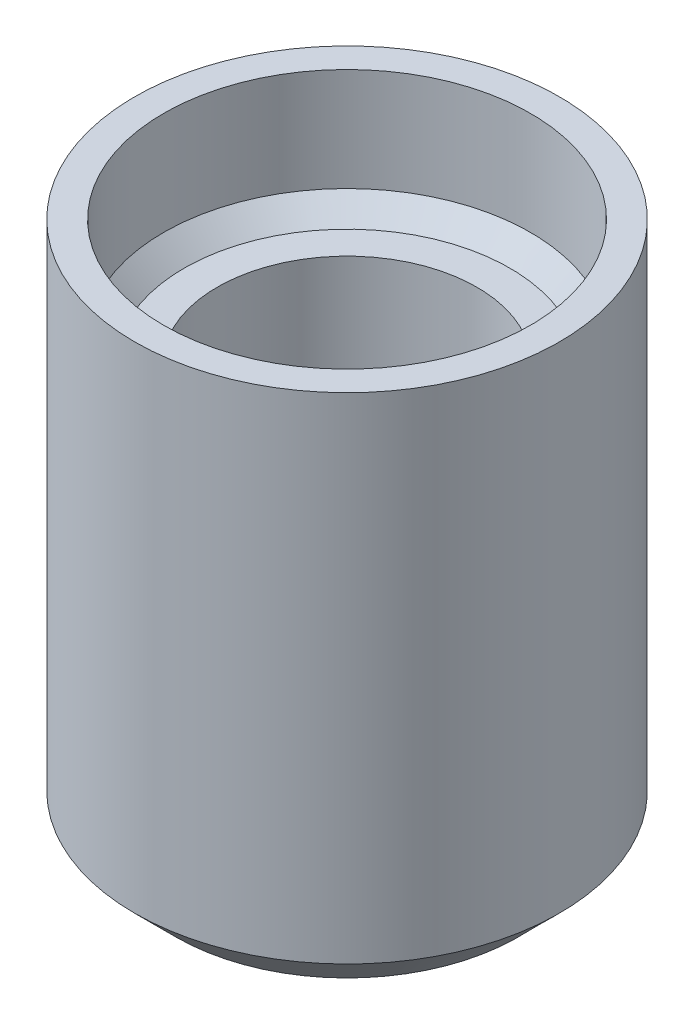
SolidWorks part; units mm, degrees
ref_plane "Front Plane" through (0, 0, 0) normal (0, 0, 1) x (1, 0, 0)
ref_plane "Top Plane" through (0, 0, 0) normal (0, 1, 0) x (1, 0, 0)
ref_plane "Right Plane" through (0, 0, 0) normal (1, 0, 0) x (0, 0, -1)
sketch "Sketch1" plane through (0, 0, 0) normal (0, 1, 0) x (1, 0, 0)
  line L0 (-2.6833, -1.65) -> (2.6833, -1.65)
  circle A0 centre (0, 0) radius 3.15
  circle A1 centre (0, 0) radius 5.15
  dimension "D1" = 6.3
  dimension "D3" = 1.65
  dimension "D2" = 2
extrude "Boss-Extrude1" add sketch "Sketch1" along normal blind 10 contours A1 A0 | L0 A0
sketch "Sketch2" plane through (0, 0, 0) normal (0, -1, 0) x (1, 0, 0)
  circle A1 centre (0, 0) radius 5.15
  circle A2 centre (0, 0) radius 5.15
  dimension "D1" = 0
extrude "Boss-Extrude2" add sketch "Sketch2" against normal blind 2
sketch "Sketch4" plane through (0, 10, 0) normal (0, 1, 0) x (1, 0, 0)
  circle A0 centre (0, 0) radius 4.45
  circle A1 centre (0, 0) radius 5.15
  circle A2 centre (0, 0) radius 5.15
  dimension "D1" = 0
  dimension "D2" = 0.7
extrude "Boss-Extrude3" add sketch "Sketch4" along normal blind 3
chamfer "Chamfer1" distance 1 angle 45 1 edges at (0, 0, 5.15)
chamfer "Chamfer2" distance 0.5 angle 45 1 edges at (0, 10, 4.45)
equation "\"ID\"= 6.3"
equation "\"notch\"= 6.3 / 2 - 1.5"
equation "\"D3@Sketch1\"=\"notch\""
